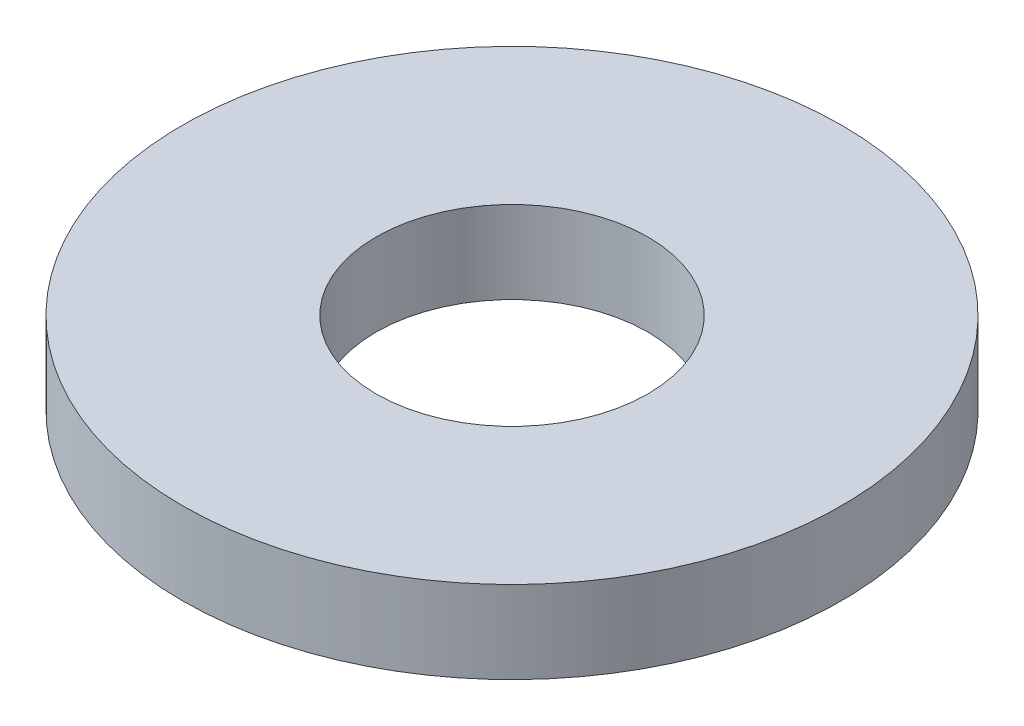
SolidWorks part; units mm, degrees
ref_plane "Alzado" through (0, 0, 0) normal (0, 0, 1) x (1, 0, 0)
ref_plane "Planta" through (0, 0, 0) normal (0, 1, 0) x (1, 0, 0)
ref_plane "Vista lateral" through (0, 0, 0) normal (1, 0, 0) x (0, 0, -1)
sketch "Croquis1" plane through (0, 0, 0) normal (0, 1, 0) x (1, 0, 0)
  circle A0 centre (0, 0) radius 4
  dimension "D1" = 8
extrude "Saliente-Extruir1" add sketch "Croquis1" along normal blind 1
sketch "Croquis2" plane through (0, 1, 0) normal (0, 1, 0) x (1, 0, 0)
  circle A0 centre (0, 0) radius 1.65
extrude "Cortar-Extruir1" cut sketch "Croquis2" against normal through all
